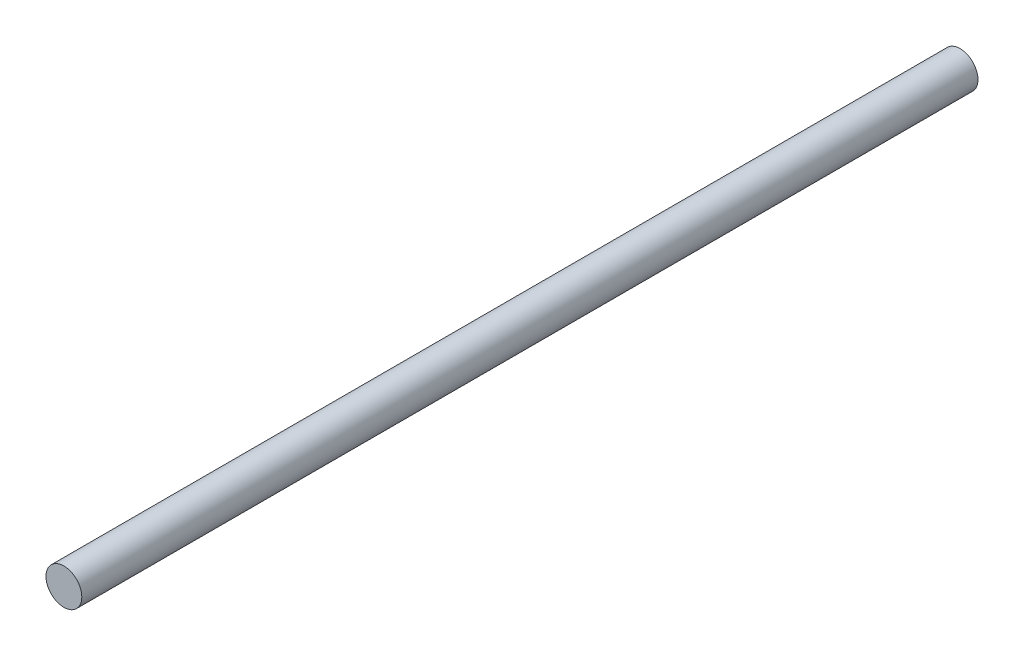
SolidWorks part; units mm, degrees
ref_plane "Plano frontal" through (0, 0, 0) normal (0, 0, 1) x (1, 0, 0)
ref_plane "Plano superior" through (0, 0, 0) normal (0, 1, 0) x (1, 0, 0)
ref_plane "Plano direito" through (0, 0, 0) normal (1, 0, 0) x (0, 0, -1)
sketch "Esboço1" plane through (0, 0, 0) normal (0, 0, 1) x (1, 0, 0)
  circle A0 centre (0, 0) radius 4
  dimension "D1" = 8
extrude "Ressalto-extrusão1" add sketch "Esboço1" along normal blind 200
